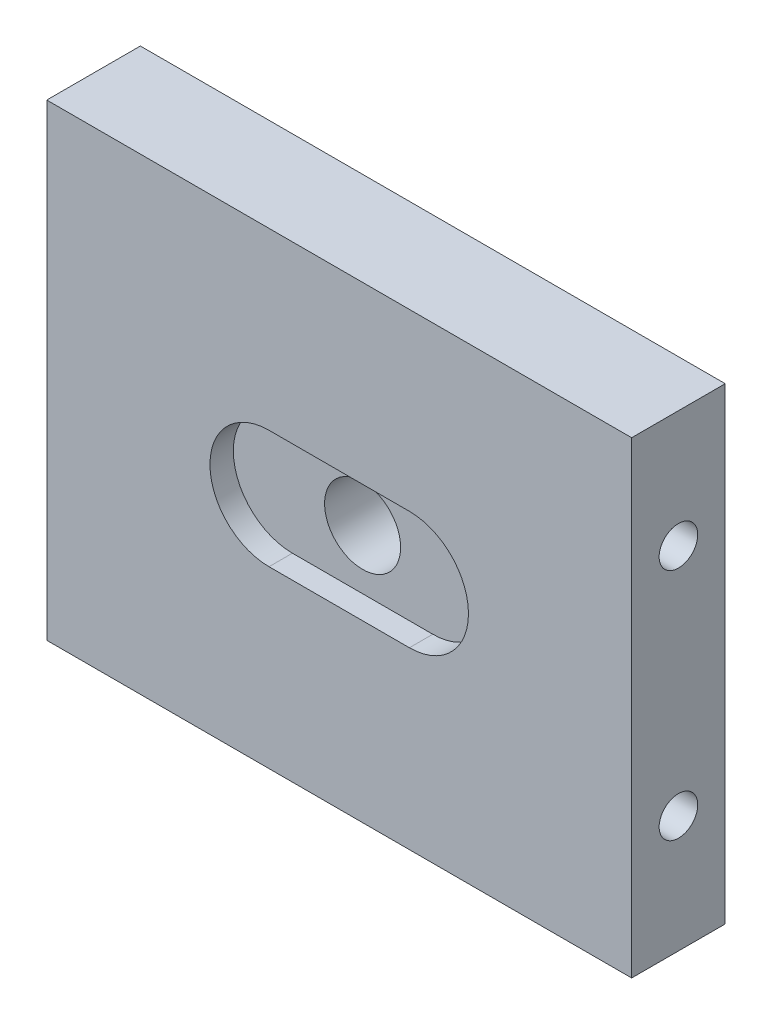
SolidWorks part; units mm, degrees
material "6061 Сплав"
ref_plane "Front" through (0, 0, 0) normal (0, 0, 1) x (1, 0, 0)
ref_plane "Top" through (0, 0, 0) normal (0, 1, 0) x (1, 0, 0)
ref_plane "Right" through (0, 0, 0) normal (1, 0, 0) x (0, 0, -1)
sketch "Эскиз1" plane through (0, 0, 0) normal (0, 0, 1) x (1, 0, 0)
  line L1 (-25, 20) -> (25, 20)
  line L2 (-25, 20) -> (-25, -20)
  line L3 (-25, -20) -> (25, -20)
  line L4 (25, 20) -> (25, -20)
  line L5 (-25, 20) -> (25, -20) construction
  line L6 (-25, -20) -> (25, 20) construction
  point P0 (0, 0)
  dimension "D1" = 50
  dimension "D2" = 40
extrude "Бобышка-Вытянуть1" add sketch "Эскиз1" along normal blind 8
sketch "Эскиз2" plane through (0, 0, 8) normal (0, 0, 1) x (1, 0, 0)
  line L0 (-6, 5.05) -> (6, 5.05)
  line L1 (6, -5.05) -> (-6, -5.05)
  line L2 (25, 20) -> (-25, 20) construction
  line L4 (-25, 20) -> (-25, -20) construction
  arc A0 (-6, 5.05) -> (-6, -5.05) centre (-6, 0) ccw
  arc A1 (6, 5.05) -> (6, -5.05) centre (6, 0) cw
  dimension "D1" = 10.1
  dimension "D2" = 12
  dimension "D3" = 14.95
  dimension "D4" = 19
extrude "Вырез-Вытянуть1" cut sketch "Эскиз2" against normal blind 2
sketch "Эскиз3" plane through (0, 0, 6) normal (0, 0, 1) x (1, 0, 0)
  circle A0 centre (0, 0) radius 3.25
extrude "Вырез-Вытянуть2" cut sketch "Эскиз3" against normal blind 10
sketch "Эскиз4" plane through (25, 0, 0) normal (1, 0, 0) x (0, 0, -1)
  line L0 (-8, -20) -> (0, -20) construction
  line L1 (-8, 20) -> (0, 20) construction
  line L2 (0, -20) -> (0, 20) construction
  circle A0 centre (-4, -10) radius 1.65
  circle A1 centre (-4, 10) radius 1.65
  point P4 (-4, -20)
  dimension "D1" = 10
  dimension "D2" = 10
  dimension "D3" = 4
  dimension "D4" = 4
extrude "Вырез-Вытянуть3" cut sketch "Эскиз4" against normal blind 15
